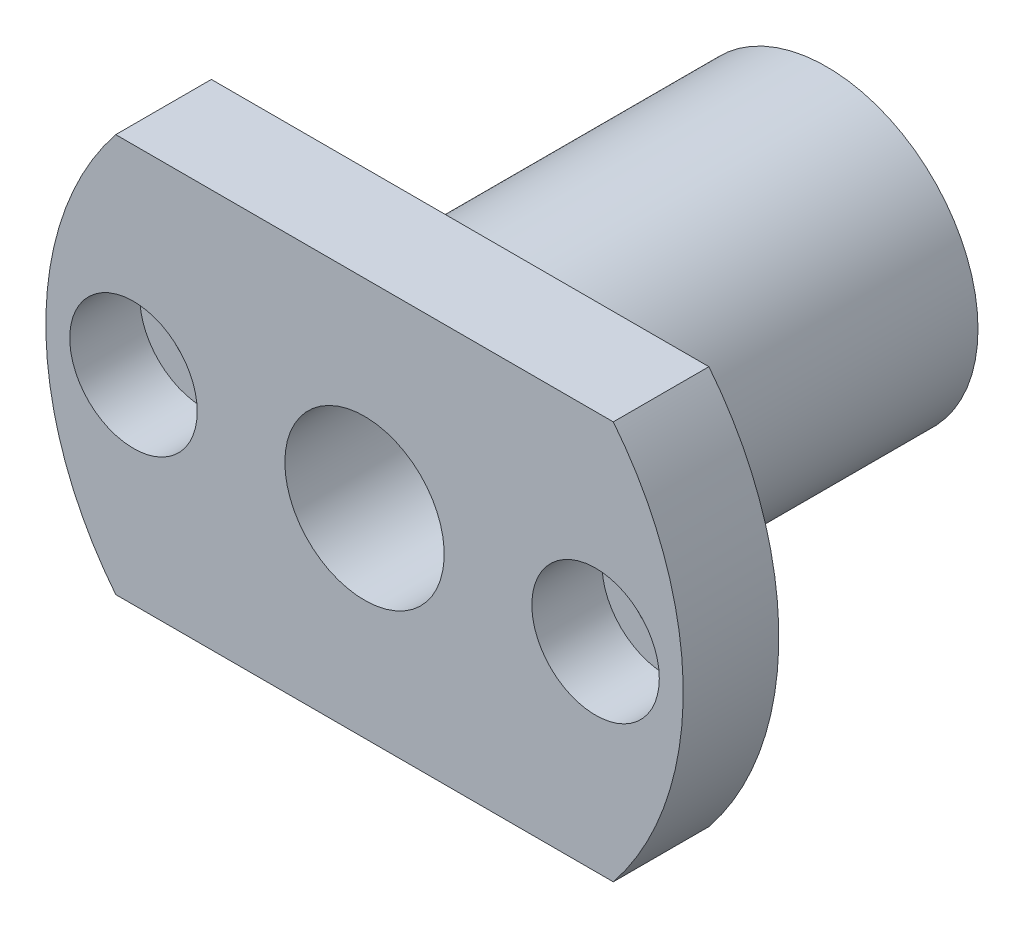
SolidWorks part; units mm, degrees
ref_plane "前视基准面" through (0, 0, 0) normal (0, 0, 1) x (1, 0, 0)
ref_plane "上视基准面" through (0, 0, 0) normal (0, 1, 0) x (1, 0, 0)
ref_plane "右视基准面" through (0, 0, 0) normal (1, 0, 0) x (0, 0, -1)
sketch "草图1" plane through (0, 0, 0) normal (0, -1, 0) x (0, 0, 1)
  line L0 (0, 0) -> (68087.4913, 0) construction
  line L1 (0, 5) -> (29, 5)
  line L2 (29, 5) -> (29, 20)
  line L3 (23, 9.5) -> (23, 20)
  line L4 (23, 20) -> (29, 20)
  line L11 (23, 9.5) -> (0, 9.5)
  line L12 (0, 9.5) -> (0, 5)
  dimension "D1" = 5
  dimension "D2" = 9.5
  dimension "D3" = 29
  dimension "D4" = 20
  dimension "D5" = 6
revolve "旋转1" add sketch "草图1" angle 360 about L0
sketch "草图2" plane through (0, 0, 29) normal (0, 0, 1) x (1, 0, 0)
  line L1 (20, -12.5) -> (-20, -12.5)
  line L2 (20, -12.5) -> (20, 12.5)
  line L3 (20, 12.5) -> (-20, 12.5)
  line L4 (-20, -12.5) -> (-20, 12.5)
  line L5 (20, -12.5) -> (-20, 12.5) construction
  line L6 (20, 12.5) -> (-20, -12.5) construction
  circle A0 centre (0, 0) radius 20 construction
  point P0 (0, 0)
  dimension "D1" = 25
extrude "切除-拉伸1" cut sketch "草图2" against normal up to surface (6 mm away) flip side to cut up to face at (-9.5, 0, 23)
hole_wizard "孔1" positions "草图4" profile "草图3" legacy end condition up to next
sketch "草图4" plane through (0, 0, 29) normal (0, 0, 1) x (1, 0, 0)
  line L3 (-14.5, 0) -> (14.5, 0) construction
  point P8 (-14.5, 0)
  point P10 (14.5, 0)
  dimension "D1" = 29
sketch "草图3" plane through (-14.5, 0, 29) normal (1, 0, 0) x (0, -1, 0)
  line L0 (0, 0) -> (0, 6)
  line L1 (0, 6) -> (2.25, 6)
  line L2 (2.25, 6) -> (2.25, 4.4)
  line L3 (2.25, 4.4) -> (4, 4.4)
  line L4 (4, 4.4) -> (4, 0)
  line L5 (4, 0) -> (0, 0)
  line L6 (0, 110) -> (0, -10) construction
  dimension "直径" = 4.5
  dimension "深度" = 6
  dimension "柱坑直径" = 8
  dimension "柱坑深度" = 4.4
